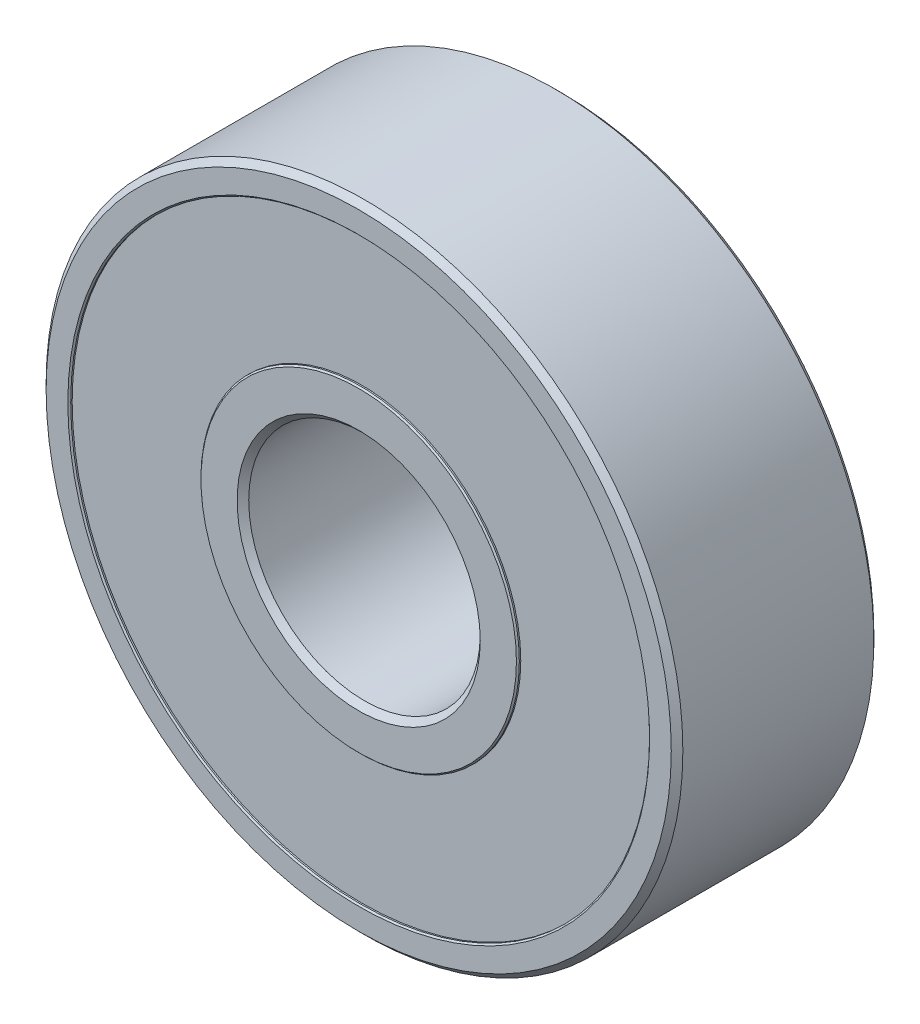
SolidWorks part; units mm, degrees
ref_plane "Front Plane" through (0, 0, 0) normal (0, 0, 1) x (1, 0, 0)
ref_plane "Top Plane" through (0, 0, 0) normal (0, 1, 0) x (1, 0, 0)
ref_plane "Right Plane" through (0, 0, 0) normal (1, 0, 0) x (0, 0, -1)
ref_plane "Plane1" through (0, 0, 0) normal (0, -1, 0) x (1, 0, 0)
sketch "Sketch1" plane through (0, 0, 0) normal (0, -1, 0) x (1, 0, 0)
  line L0 (11, 7) -> (0, 7)
  line L1 (0, 7) -> (0, 0)
  line L2 (0, 0) -> (11, 0)
  line L3 (11, 0) -> (11, 7)
  line L4 (0, 7) -> (0, 0) construction
revolve "Revolve1" add sketch "Sketch1" angle 360 about L4
sketch "Sketch2" plane through (0, 0, 0) normal (0, 0, -1) x (-1, 0, 0)
  circle A0 centre (0, 0) radius 10.05
extrude "Cut-Extrude1" cut sketch "Sketch2" against normal blind 0.05 draft 45
sketch "Sketch3" plane through (0, 0, 0.05) normal (0, 0, -1) x (-1, 0, 0)
  circle A0 centre (0, 0) radius 10
extrude "Cut-Extrude2" cut sketch "Sketch3" against normal blind 0.05
sketch "Sketch4" plane through (0, 0, 0.1) normal (0, 0, -1) x (-1, 0, 0)
  circle A0 centre (0, 0) radius 5.5
extrude "Boss-Extrude1" add sketch "Sketch4" along normal blind 0.05
sketch "Sketch5" plane through (0, 0, 0.05) normal (0, 0, -1) x (-1, 0, 0)
  circle A0 centre (0, 0) radius 5.5
extrude "Boss-Extrude2" add sketch "Sketch5" along normal blind 0.05 draft 45
sketch "Sketch6" plane through (0, 0, 7) normal (0, 0, 1) x (1, 0, 0)
  circle A0 centre (0, 0) radius 10.05
extrude "Cut-Extrude3" cut sketch "Sketch6" against normal blind 0.05 draft 45
sketch "Sketch7" plane through (0, 0, 6.95) normal (0, 0, 1) x (1, 0, 0)
  circle A0 centre (0, 0) radius 10
extrude "Cut-Extrude4" cut sketch "Sketch7" against normal blind 0.05
sketch "Sketch8" plane through (0, 0, 0) normal (0, 1, 0) x (1, 0, 0)
  line L0 (5.5, -6.9) -> (0, -6.9)
  line L1 (0, -6.9) -> (0, -7)
  line L2 (0, -7) -> (5.45, -7)
  line L3 (5.45, -7) -> (5.5, -6.95)
  line L4 (5.5, -6.95) -> (5.5, -6.9)
  line L5 (0, -6.9) -> (0, -7) construction
revolve "Revolve2" add sketch "Sketch8" angle 360 about L5
hole_wizard "Ø8.0 (8) Diameter Hole1" positions "Sketch10" profile "Sketch9" hole size "Ø8.0" standard "ANSI Metric"
sketch "Sketch10" plane through (0, 0, 7) normal (0, 0, 1) x (1, 0, 0)
  point P0 (0, 0)
sketch "Sketch9" plane through (0, 0, 7) normal (1, 0, 0) x (0, -1, 0)
  line L0 (0, 0) -> (0, 7)
  line L1 (0, 7) -> (4, 7)
  line L2 (4, 7) -> (4, 0)
  line L5 (4, 0) -> (0, 0)
  line L11 (0, -6.35) -> (0, 107.95) construction
  dimension "Thru Hole Dia." = 8
  dimension "Thru Hole Depth" = 7
chamfer "Chamfer1" distance 0.2 angle 45 4 edges at (-11, 0, 0) (-11, 0, 7) (4, 0, 0) (4, 0, 7)
ref_plane "Plane2" through (0, 0, 3.5) normal (0, 0, 1) x (1, 0, 0)
